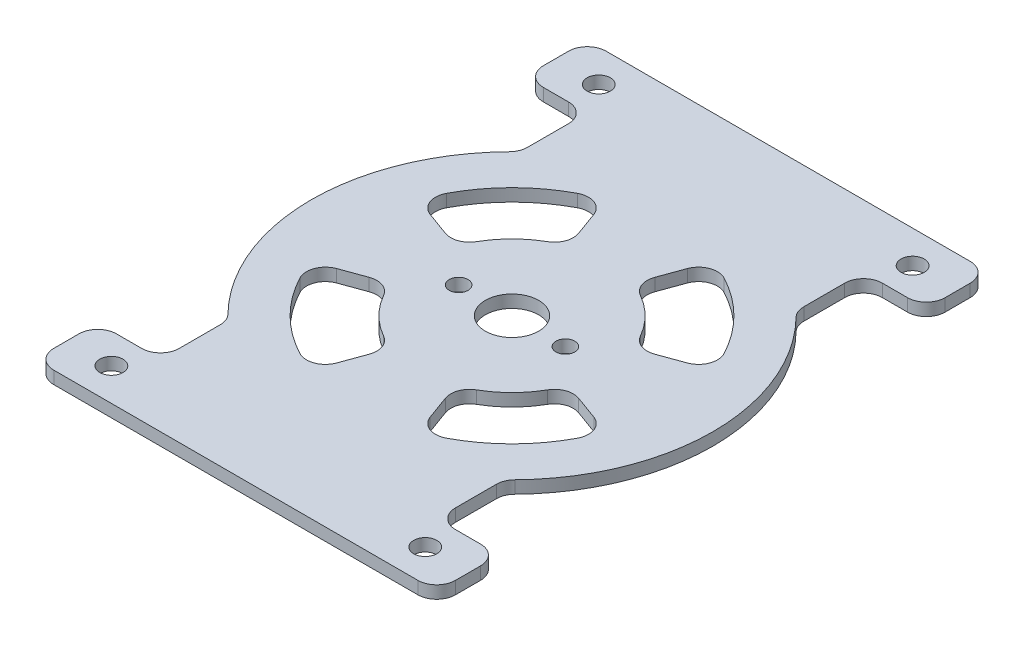
SolidWorks part; units mm, degrees
material "Acrylic (Medium-high impact)"
ref_plane "Front Plane" through (0, 0, 0) normal (0, 0, 1) x (1, 0, 0)
ref_plane "Top Plane" through (0, 0, 0) normal (0, 1, 0) x (1, 0, 0)
ref_plane "Right Plane" through (0, 0, 0) normal (1, 0, 0) x (0, 0, -1)
sketch "Sketch1" plane through (0, 0, 0) normal (0, 1, 0) x (1, 0, 0)
  line L0 (-32, 44) -> (-32, 37)
  line L1 (32, -44) -> (-32, -44)
  line L3 (32, 44) -> (-32, 44)
  line L5 (32, -44) -> (-32, 44) construction
  line L6 (32, 44) -> (-32, -44) construction
  line L7 (-29, 34) -> (-25, 34)
  line L8 (-22, 31) -> (-22, 24.4949)
  line L9 (-32, 34) -> (-32, 44)
  line L10 (32, 44) -> (32, 37)
  line L11 (29, 34) -> (25, 34)
  line L12 (22, 31) -> (22, 24.4949)
  line L13 (-55, 0) -> (55, 0) construction
  line L14 (-22, -31) -> (-22, -24.4949)
  line L15 (-29, -34) -> (-25, -34)
  line L16 (-32, -44) -> (-32, -37)
  line L17 (32, -44) -> (32, -37)
  line L18 (22, -31) -> (22, -24.4949)
  line L19 (29, -34) -> (25, -34)
  circle A0 centre (0, 0) radius 4.25
  arc A1 (-22.8571, 22.3953) -> (-22.8571, -22.3953) centre (0, 0) ccw
  arc A3 (22.8571, -22.3953) -> (22.8571, 22.3953) centre (0, 0) ccw
  arc A4 (-22, 24.4949) -> (-22.8571, 22.3953) centre (-25, 24.4949) cw
  arc A5 (-32, 37) -> (-29, 34) centre (-29, 37) ccw
  arc A6 (-25, 34) -> (-22, 31) centre (-25, 31) cw
  arc A7 (32, 37) -> (29, 34) centre (29, 37) cw
  arc A8 (25, 34) -> (22, 31) centre (25, 31) ccw
  arc A9 (22, 24.4949) -> (22.8571, 22.3953) centre (25, 24.4949) ccw
  arc A10 (32, -37) -> (29, -34) centre (29, -37) ccw
  arc A11 (22, -31) -> (25, -34) centre (25, -31) ccw
  arc A12 (22, -24.4949) -> (22.8571, -22.3953) centre (25, -24.4949) cw
  arc A13 (-22, -24.4949) -> (-22.8571, -22.3953) centre (-25, -24.4949) ccw
  arc A14 (-22, -31) -> (-25, -34) centre (-25, -31) cw
  arc A15 (-29, -34) -> (-32, -37) centre (-29, -37) ccw
  point P0 (0, 0)
  point P25 (-22, 23.2379)
  point P31 (-22, 34)
  point P34 (32, 34)
  point P37 (22, 34)
  point P40 (22, 23.2379)
  point P43 (32, -34)
  point P46 (22, -34)
  point P49 (22, -23.2379)
  point P52 (-22, -23.2379)
  point P55 (-22, -34)
  point P58 (-32, -34)
  dimension "D3" = 8.5
  dimension "D5" = 64
  dimension "D10" = 3
  dimension "D1" = 64
  dimension "D2" = 88
  dimension "D6" = 10
  dimension "D7" = 10
  dimension "D8" = 10
  dimension "D9" = 10
extrude "Boss-Extrude1" add sketch "Sketch1" along normal blind 2 contours L15 A15 L16 L1 L17 A10 L19 A11 L18 A12 A3 A9 L12 A8 L11 A7 L10 L3 L0 A5 L7 A6 L8 A4 A1 A13 L14 A14 A0
sketch "Sketch2" plane through (0, 2, 0) normal (0, 1, 0) x (1, 0, 0)
  line L0 (0, 34.8617) -> (0, -39.3717) construction
  line L1 (-36.4463, 0) -> (53.8771, 0) construction
  line L2 (42.9011, -15.6147) -> (0, 0)
  line L3 (10.8296, -29.754) -> (0, 0)
  line L4 (-6.0703, 16.6779) -> (-7.4542, 20.4801)
  line L5 (-16.6779, 6.0703) -> (-20.4801, 7.4542)
  arc A0 (-11.6741, 22.1069) -> (-22.1069, 11.6741) centre (0, 0) ccw
  arc A1 (-7.4078, 13.0432) -> (-13.0432, 7.4078) centre (0, 0) ccw
  arc A2 (-22.1069, 11.6741) -> (-20.4801, 7.4542) centre (-19.4541, 10.2732) ccw
  arc A3 (-13.0432, 7.4078) -> (-16.6779, 6.0703) centre (-15.6518, 8.8893) cw
  arc A4 (-7.4078, 13.0432) -> (-6.0703, 16.6779) centre (-8.8893, 15.6518) ccw
  arc A5 (-11.6741, 22.1069) -> (-7.4542, 20.4801) centre (-10.2732, 19.4541) cw
  point P11 (0, 0)
  point P12 (-23.4923, 8.5505)
  point P15 (0, 0)
  point P20 (-14.0954, 5.1303)
  point P23 (-5.1303, 14.0954)
  point P26 (-8.5505, 23.4923)
  dimension "D1" = 50
  dimension "D2" = 30
  dimension "D5" = 3
  dimension "D3" = 20
  dimension "D4" = 20
extrude "Cut-Extrude1" cut sketch "Sketch2" against normal blind 5 contours A5 A0 A2 L5 A3 A1 A4 L4
pattern_circular "CirPattern1" count 4 over 360 about axis through (0, 0, 0) along (0, 1, 0) of "Cut-Extrude1"
sketch "Sketch3" plane through (0, 2, 0) normal (0, 1, 0) x (1, 0, 0)
  line L0 (-12.9208, 0) -> (20.4782, 0) construction
  circle A0 centre (-8.5, 0) radius 1.5
  circle A1 centre (8.5, 0) radius 1.5
  dimension "D3" = 3
  dimension "D1" = 8.5
  dimension "D2" = 17
extrude "Cut-Extrude2" cut sketch "Sketch3" against normal blind 5
sketch "Sketch5" plane through (0, 2, 0) normal (0, 1, 0) x (1, 0, 0)
  circle A0 centre (25, 38.82) radius 1.85
  circle A1 centre (-25, 38.82) radius 1.85
  circle A2 centre (-25, -38.82) radius 1.85
  circle A3 centre (25, -38.82) radius 1.85
  dimension "D1" = 3.7
extrude "Cut-Extrude3" cut sketch "Sketch5" against normal blind 5
fillet "Fillet1" radius 3 4 edges at (32, 1, -44) (-32, 1, -44) (-32, 1, 44) (32, 1, 44)
